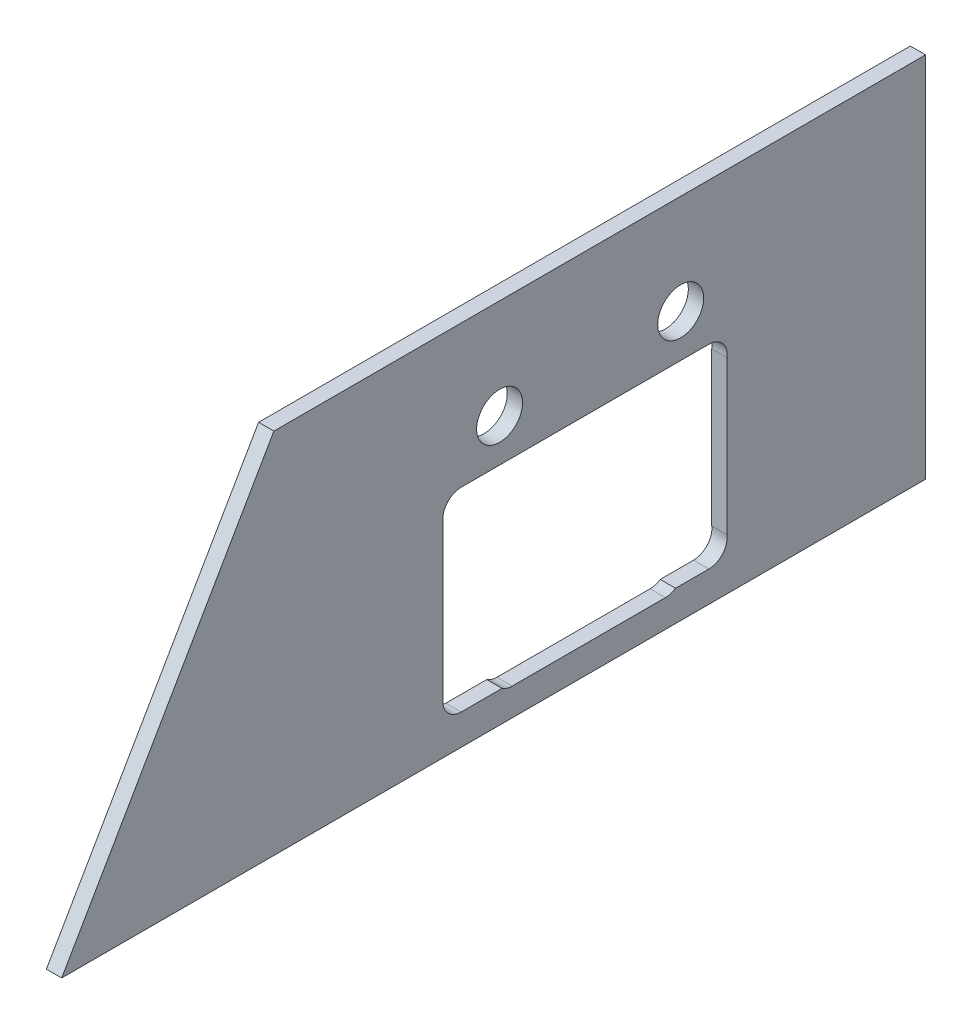
SolidWorks part; units mm, degrees
ref_plane "Спереди" through (0, 0, 0) normal (0, 0, 1) x (1, 0, 0)
ref_plane "Сверху" through (0, 0, 0) normal (0, 1, 0) x (1, 0, 0)
ref_plane "Справа" through (0, 0, 0) normal (1, 0, 0) x (0, 0, -1)
sketch "Эскиз1" plane through (0, 0, 0) normal (1, 0, 0) x (0, 0, -1)
  line L0 (28.2163, 4.5072) -> (28.2163, -19.5)
  line L1 (28.2163, -19.5) -> (-28.2163, -19.5)
  line L2 (-28.2163, -19.5) -> (-14.3558, 4.5072)
  line L4 (-14.3558, 4.5072) -> (28.2163, 4.5072)
extrude "Бобышка-Вытянуть1" add sketch "Эскиз1" along normal blind 1
sketch "Эскиз3" plane through (0, 0, 0) normal (-1, 0, 0) x (0, 0, 1)
  line L8 (-1.2163, -7.8) -> (-11.2163, -7.8)
  line L9 (-12.4163, -16.5) -> (-12.4163, -9)
  line L10 (-1.2163, -17.7) -> (-11.2163, -17.7)
  line L11 (-0.0163, -16.5) -> (-0.0163, -9)
  arc A4 (-11.2163, -7.8) -> (-12.4163, -9) centre (-11.2163, -9) ccw
  arc A5 (-12.4163, -16.5) -> (-11.2163, -17.7) centre (-11.2163, -16.5) ccw
  arc A6 (-1.2163, -17.7) -> (-0.0163, -16.5) centre (-1.2163, -16.5) ccw
  arc A7 (-0.0163, -9) -> (-1.2163, -7.8) centre (-1.2163, -9) ccw
  point P3 (-12.2163, -13.5)
  point P6 (-6.2163, -8)
  point P9 (-0.2163, -13.5)
  point P12 (-6.2163, -17.5)
extrude "Вырез-Вытянуть1" cut sketch "Эскиз3" against normal through all
sketch "Эскиз5" plane through (0, 0, 0) normal (-1, 0, 0) x (0, 0, 1)
  circle A0 centre (-12.2163, -2) radius 1.5
  circle A1 centre (-0.3875, -2) radius 1.5
extrude "Вырез-Вытянуть2" cut sketch "Эскиз5" against normal through all
sketch "Sketch2" plane through (1, 0, 0) normal (1, 0, 0) x (0, 0, -1)
  line L4 (14.0586, -4.786) -> (-2.125, -4.786)
  line L5 (-3.3097, -6.1289) -> (-3.3097, -16.1542)
  line L6 (-2.1254, -17.5) -> (14.0583, -17.5)
  line L7 (15.2463, -16.1571) -> (15.2463, -6.1318)
  line L8 (14.0586, -4.786) -> (-2.125, -4.786)
  line L9 (-3.3097, -6.1289) -> (-3.3097, -16.1542)
  line L10 (-2.1254, -17.5) -> (14.0583, -17.5)
  line L11 (15.2463, -16.1571) -> (15.2463, -6.1318)
  arc A4 (-2.125, -4.786) -> (-3.3097, -6.1289) centre (-2.1182, -5.986) ccw
  arc A5 (-3.3097, -16.1542) -> (-2.1254, -17.5) centre (-2.1186, -16.3) ccw
  arc A6 (14.0583, -17.5) -> (15.2463, -16.1571) centre (14.0549, -16.3) ccw
  arc A7 (15.2463, -6.1318) -> (14.0586, -4.786) centre (14.0552, -5.986) ccw
  arc A8 (-2.125, -4.786) -> (-3.3097, -6.1289) centre (-2.1182, -5.986) ccw
  arc A9 (-3.3097, -16.1542) -> (-2.1254, -17.5) centre (-2.1186, -16.3) ccw
  arc A10 (14.0583, -17.5) -> (15.2463, -16.1571) centre (14.0549, -16.3) ccw
  arc A11 (15.2463, -6.1318) -> (14.0586, -4.786) centre (14.0552, -5.986) ccw
  dimension "D1" = 0
extrude "Cut-Extrude1" cut sketch "Sketch2" against normal up to surface (1 mm away) up to face at (0, -2, -10.7163)
